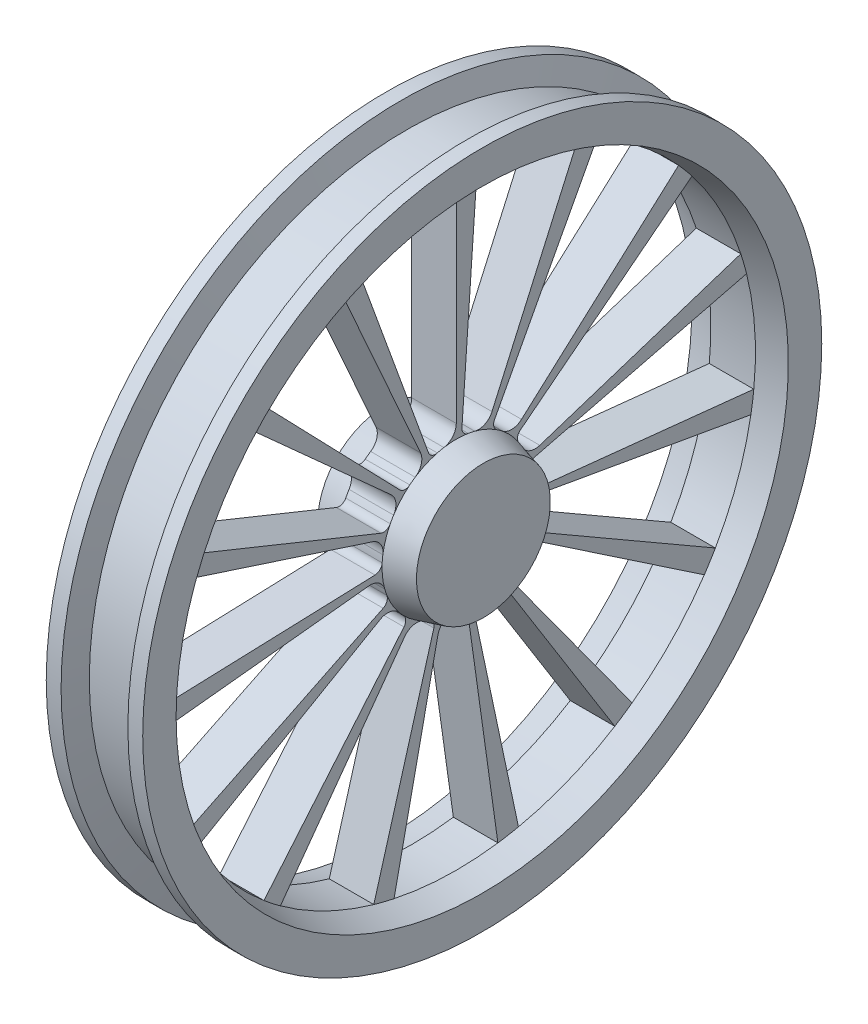
SolidWorks part; units mm, degrees
material "1060 Alloy"
ref_plane "Front Plane" through (0, 0, 0) normal (0, 0, 1) x (1, 0, 0)
ref_plane "Top Plane" through (0, 0, 0) normal (0, 1, 0) x (1, 0, 0)
ref_plane "Right Plane" through (0, 0, 0) normal (1, 0, 0) x (0, 0, -1)
sketch "Sketch1" plane through (0, 0, 0) normal (0, 0, 1) x (1, 0, 0)
  line L0 (-3022.3213, 0) -> (3022.3213, 0) construction
  line L1 (-1689.6209, 0) -> (1689.6209, 0)
  line L2 (1689.6209, 0) -> (1689.6209, 2291.4447)
  line L3 (1689.6209, 2291.4447) -> (762, 2540)
  line L4 (762, 2540) -> (762, 10239.2932)
  line L5 (762, 10239.2932) -> (1651, 10477.5)
  line L6 (1651, 10477.5) -> (1651, 11620.5)
  line L7 (1651, 11620.5) -> (1143, 11620.5)
  line L8 (1143, 11620.5) -> (938.8227, 10858.5)
  line L9 (0, 0) -> (0, 762) construction
  line L10 (938.8227, 10858.5) -> (0, 10858.5)
  line L12 (0, 10858.5) -> (0, 0) construction
  line L13 (-1689.6209, 0) -> (-1689.6209, 2291.4447)
  line L14 (-1689.6209, 2291.4447) -> (-762, 2540)
  line L15 (-762, 2540) -> (-762, 10239.2932)
  line L16 (-762, 10239.2932) -> (-1651, 10477.5)
  line L17 (-1651, 10477.5) -> (-1651, 11620.5)
  line L18 (-1651, 11620.5) -> (-1143, 11620.5)
  line L19 (-1143, 11620.5) -> (-938.8227, 10858.5)
  line L20 (-938.8227, 10858.5) -> (0, 10858.5)
  point P4 (0, 0)
  dimension "D1" = 1651
  dimension "D2" = 15
  dimension "D3" = 15
  dimension "D4" = 1143
  dimension "D5" = 508
  dimension "D6" = 15
  dimension "D7" = 762
  dimension "D8" = 11620.5
  dimension "D9" = 2540
  dimension "D10" = 1524
revolve "Revolve1" add sketch "Sketch1" angle 360 about L0
sketch "Sketch2" plane through (-762, 0, 0) normal (-1, 0, 0) x (0, 0, 1)
  line L0 (0, 3005.3685) -> (0, 10239.2932)
  line L1 (951.6473, 2614.6295) -> (3502.0445, 9621.7882)
  line L2 (0, 0) -> (868.7312, 2386.8193)
  line L3 (1222.3935, 2745.5408) -> (4164.6957, 9354.0598)
  line L4 (1932.8387, 2001.5131) -> (7112.8107, 7365.5311)
  line L5 (2233.4241, 2010.9841) -> (7609.2777, 6851.4244)
  line L6 (2579.8247, 1042.3168) -> (9493.7073, 3835.7067)
  line L7 (2858.2753, 928.71) -> (9738.1465, 3164.1156)
  line L8 (2780.7356, -97.1054) -> (10233.0557, -357.3462)
  line L9 (2988.9048, -314.1466) -> (10183.2012, -1070.2976)
  line L10 (2500.8321, -1219.7373) -> (9203.0157, -4488.6107)
  line L11 (2602.7255, -1502.6843) -> (8867.488, -5119.6466)
  line L12 (1788.5119, -2131.4655) -> (6581.6908, -7843.7536)
  line L13 (1766.5113, -2431.3942) -> (6018.5055, -8283.7622)
  line L14 (766.9418, -2674.6439) -> (2822.3317, -9842.6403)
  line L15 (624.8513, -2939.694) -> (2128.8688, -10015.54)
  line L16 (-387.2395, -2755.3522) -> (-1425.0342, -10139.6451)
  line L17 (-624.8513, -2939.694) -> (-2128.8688, -10015.54)
  line L18 (-1474.4636, -2359.635) -> (-5425.9987, -8683.4131)
  line L19 (-1766.5113, -2431.3942) -> (-6018.5055, -8283.7622)
  line L20 (-2306.7395, -1555.9154) -> (-8488.7588, -5725.7401)
  line L21 (-2602.7255, -1502.6843) -> (-8867.488, -5119.6466)
  line L22 (-2740.1592, -483.164) -> (-10083.7353, -1778.0346)
  line L23 (-2988.9048, -314.1466) -> (-10183.2012, -1070.2976)
  line L24 (-2699.7805, 673.1309) -> (-9935.1424, 2477.1092)
  line L25 (-2858.2753, 928.71) -> (-9738.1465, 3164.1156)
  line L26 (-2192.5852, 1713.0353) -> (-8068.6731, 6303.9383)
  line L27 (-2233.4241, 2010.9841) -> (-7609.2777, 6851.4244)
  line L28 (-1306.272, 2456.7404) -> (-4807.057, 9040.7593)
  line L29 (-1222.3935, 2745.5408) -> (-4164.6957, 9354.0598)
  line L30 (-194.0925, 2775.6527) -> (-714.257, 10214.3508)
  arc A0 (648.1503, 2455.9115) -> (951.6473, 2614.6295) centre (712.9654, 2701.5026) ccw
  circle A1 centre (0, 0) radius 10239.2932
  arc A2 (3502.0445, 9621.7882) -> (0, 10239.2932) centre (0, 0) ccw
  circle A3 centre (0, 0) radius 2540 construction
  arc A4 (648.1503, 2455.9115) -> (423.3333, 2504.4738) centre (0, 0) ccw
  arc A5 (0, 3005.3685) -> (423.3333, 2504.4738) centre (508, 3005.3685) ccw
  arc A6 (7112.8107, 7365.5311) -> (4164.6957, 9354.0598) centre (0, 0) ccw
  arc A7 (1222.3935, 2745.5408) -> (1405.3955, 2115.7655) centre (1686.4746, 2538.9186) ccw
  arc A8 (1591.024, 1979.9603) -> (1932.8387, 2001.5131) centre (1750.1264, 2177.9563) ccw
  arc A9 (1591.024, 1979.9603) -> (1405.3955, 2115.7655) centre (0, 0) ccw
  arc A10 (9493.7073, 3835.7067) -> (7609.2777, 6851.4244) centre (0, 0) ccw
  arc A11 (2233.4241, 2010.9841) -> (2144.452, 1361.2221) centre (2573.3424, 1633.4665) ccw
  arc A12 (2258.7951, 1161.6559) -> (2579.8247, 1042.3168) centre (2484.6746, 1277.8215) ccw
  arc A13 (2258.7951, 1161.6559) -> (2144.452, 1361.2221) centre (0, 0) ccw
  arc A14 (10233.0557, -357.3462) -> (9738.1465, 3164.1156) centre (0, 0) ccw
  arc A15 (2858.2753, 928.71) -> (2512.7133, 371.311) centre (3015.256, 445.5732) ccw
  arc A16 (2536.0001, 142.4908) -> (2780.7356, -97.1054) centre (2789.6001, 156.7398) ccw
  arc A17 (2536.0001, 142.4908) -> (2512.7133, 371.311) centre (0, 0) ccw
  arc A18 (9203.0157, -4488.6107) -> (10183.2012, -1070.2976) centre (0, 0) ccw
  arc A19 (2988.9048, -314.1466) -> (2446.5036, -682.8031) centre (2935.8043, -819.3637) ccw
  arc A20 (2374.7076, -901.3124) -> (2500.8321, -1219.7373) centre (2612.1783, -991.4436) ccw
  arc A21 (2374.7076, -901.3124) -> (2446.5036, -682.8031) centre (0, 0) ccw
  arc A22 (6581.6908, -7843.7536) -> (8867.488, -5119.6466) centre (0, 0) ccw
  arc A23 (2602.7255, -1502.6843) -> (1957.2712, -1618.8543) centre (2348.7255, -1942.6252) ccw
  arc A24 (1802.8065, -1789.2704) -> (1788.5119, -2131.4655) centre (1983.0872, -1968.1974) ccw
  arc A25 (1802.8065, -1789.2704) -> (1957.2712, -1618.8543) centre (0, 0) ccw
  arc A26 (2822.3317, -9842.6403) -> (6018.5055, -8283.7622) centre (0, 0) ccw
  arc A27 (1766.5113, -2431.3942) -> (1129.6089, -2274.9909) centre (1355.5307, -2729.9891) ccw
  arc A28 (919.1839, -2367.8473) -> (766.9418, -2674.6439) centre (1011.1023, -2604.6321) ccw
  arc A29 (919.1839, -2367.8473) -> (1129.6089, -2274.9909) centre (0, 0) ccw
  arc A30 (-1425.0342, -10139.6451) -> (2128.8688, -10015.54) centre (0, 0) ccw
  arc A31 (624.8513, -2939.694) -> (106.6269, -2537.761) centre (127.9523, -3045.3132) ccw
  arc A32 (-123.374, -2537.0019) -> (-387.2395, -2755.3522) centre (-135.7114, -2790.7021) ccw
  arc A33 (-123.374, -2537.0019) -> (106.6269, -2537.761) centre (0, 0) ccw
  arc A34 (-5425.9987, -8683.4131) -> (-2128.8688, -10015.54) centre (0, 0) ccw
  arc A35 (-624.8513, -2939.694) -> (-934.7919, -2361.7291) centre (-1121.7502, -2834.0749) ccw
  arc A36 (-1144.5994, -2267.4859) -> (-1474.4636, -2359.635) centre (-1259.0594, -2494.2345) ccw
  arc A37 (-1144.5994, -2267.4859) -> (-934.7919, -2361.7291) centre (0, 0) ccw
  arc A38 (-8488.7588, -5725.7401) -> (-6018.5055, -8283.7622) centre (0, 0) ccw
  arc A39 (-1766.5113, -2431.3942) -> (-1814.5766, -1777.3328) centre (-2177.4919, -2132.7993) ccw
  arc A40 (-1967.9132, -1605.9009) -> (-2306.7395, -1555.9154) centre (-2164.7045, -1766.491) ccw
  arc A41 (-1967.9132, -1605.9009) -> (-1814.5766, -1777.3328) centre (0, 0) ccw
  arc A42 (-10083.7353, -1778.0346) -> (-8867.488, -5119.6466) centre (0, 0) ccw
  arc A43 (-2602.7255, -1502.6843) -> (-2380.6046, -885.6195) centre (-2856.7255, -1062.7434) ccw
  arc A44 (-2450.9569, -666.6411) -> (-2740.1592, -483.164) centre (-2696.0526, -733.3052) ccw
  arc A45 (-2450.9569, -666.6411) -> (-2380.6046, -885.6195) centre (0, 0) ccw
  arc A46 (-9935.1424, 2477.1092) -> (-10183.2012, -1070.2976) centre (0, 0) ccw
  arc A47 (-2988.9048, -314.1466) -> (-2535.0044, 159.2255) centre (-3042.0053, 191.0706) ccw
  arc A48 (-2510.2079, 387.8871) -> (-2699.7805, 673.1309) centre (-2761.2287, 426.6758) ccw
  arc A49 (-2510.2079, 387.8871) -> (-2535.0044, 159.2255) centre (0, 0) ccw
  arc A50 (-8068.6731, 6303.9383) -> (-9738.1465, 3164.1156) centre (0, 0) ccw
  arc A51 (-2858.2753, 928.71) -> (-2251.0789, 1176.5389) centre (-2701.2947, 1411.8467) ccw
  arc A52 (-2135.4211, 1375.346) -> (-2192.5852, 1713.0353) centre (-2348.9632, 1512.8806) ccw
  arc A53 (-2135.4211, 1375.346) -> (-2251.0789, 1176.5389) centre (0, 0) ccw
  arc A54 (-4807.057, 9040.7593) -> (-7609.2777, 6851.4244) centre (0, 0) ccw
  arc A55 (-2233.4241, 2010.9841) -> (-1577.9214, 1990.418) centre (-1893.5057, 2388.5016) ccw
  arc A56 (-1391.4007, 2124.9951) -> (-1306.272, 2456.7404) centre (-1530.5407, 2337.4946) ccw
  arc A57 (-1391.4007, 2124.9951) -> (-1577.9214, 1990.418) centre (0, 0) ccw
  arc A58 (-714.257, 10214.3508) -> (-4164.6957, 9354.0598) centre (0, 0) ccw
  arc A59 (-1222.3935, 2745.5408) -> (-631.927, 2460.1358) centre (-758.3124, 2952.163) ccw
  arc A60 (-406.7944, 2507.2133) -> (-194.0925, 2775.6527) centre (-447.4738, 2757.9346) ccw
  arc A61 (-406.7944, 2507.2133) -> (-631.927, 2460.1358) centre (0, 0) ccw
  point P127 (0, 0)
  circle M5 centre (0, 0) radius 2540
  circle M6 centre (0, 0) radius 10239.2932
  dimension "D4" = 254
  dimension "D5" = 508
  dimension "D2" = 20
  dimension "D3" = 20
  dimension "D1" = 0
  dimension "D6" = 15
extrude "Cut-Extrude1" cut sketch "Sketch2" against normal through all both and the other way through all contours A32 L16 L15 A31 M5 M6 | A36 L18 L17 A35 M5 M6 | A28 L14 L13 A27 M5 M6 | A24 L12 L11 A23 M5 M6 | A20 L10 L9 A19 M5 M6 | A16 L8 L7 A15 M5 M6 | A12 L6 L5 A11 M5 M6 | A8 L4 L3 A7 M5 M6 | L0 A5 A0 L1 M5 M6 | A60 L30 L29 A59 M5 M6 | A56 L28 L27 A55 M5 M6 | A52 L26 L25 A51 M5 M6 | A48 L24 L23 A47 M5 M6 | A44 L22 L21 A43 M5 M6 | A40 L20 L19 A39 M5 M6
equation "\"A\"= 130mm"
equation "\"B\"= 915mm"
